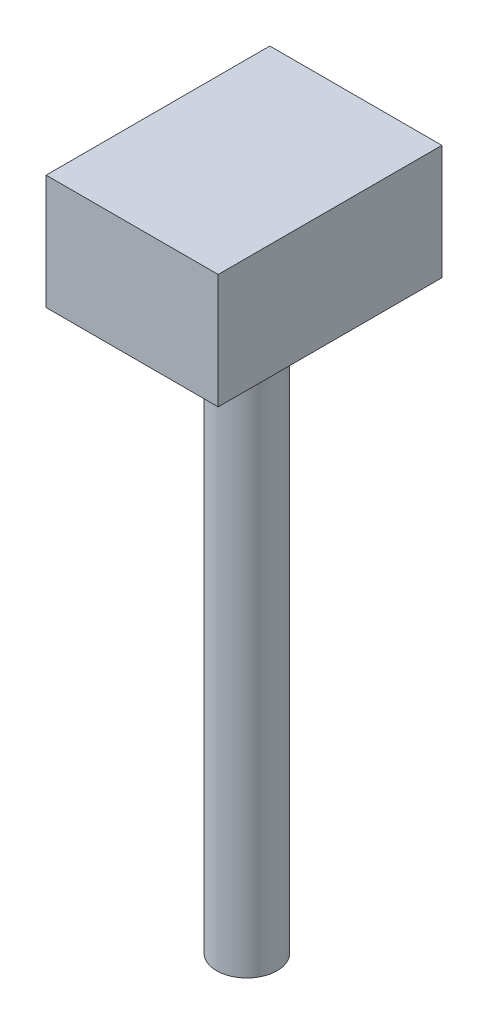
SolidWorks part; units mm, degrees
ref_plane "Front Plane" through (0, 0, 0) normal (0, 0, 1) x (1, 0, 0)
ref_plane "Top Plane" through (0, 0, 0) normal (0, 1, 0) x (1, 0, 0)
ref_plane "Right Plane" through (0, 0, 0) normal (1, 0, 0) x (0, 0, -1)
sketch "Sketch6" plane through (0, 0, 0) normal (0, 0, 1) x (1, 0, 0)
  line L1 (-24.9396, 27.929) -> (275.0604, 27.929)
  line L2 (-24.9396, 27.929) -> (-24.9396, -172.071)
  line L3 (-24.9396, -172.071) -> (275.0604, -172.071)
  line L4 (275.0604, 27.929) -> (275.0604, -172.071)
  dimension "D1" = 200
  dimension "D2" = 300
extrude "Boss-Extrude2" add sketch "Sketch6" along normal blind 400
sketch "Sketch7" plane through (0, 0, 0) normal (0, 0, -1) x (-1, 0, 0)
  line L0 (24.9396, 27.929) -> (24.9396, -172.071) construction
  line L1 (-265.0604, 22.929) -> (14.9396, 22.929)
  line L2 (-265.0604, 22.929) -> (-265.0604, -167.071)
  line L3 (-265.0604, -167.071) -> (14.9396, -167.071)
  line L4 (14.9396, 22.929) -> (14.9396, -167.071)
  line L5 (24.9396, -172.071) -> (-275.0604, -172.071) construction
  dimension "D1" = 280
  dimension "D2" = 190
  dimension "D3" = 10
  dimension "D4" = 5
extrude "Cut-Extrude1" cut sketch "Sketch7" against normal blind 390
sketch "Sketch8" plane through (0, -172.071, 0) normal (0, -1, 0) x (1, 0, 0)
  line L0 (275.0604, 400) -> (275.0604, 0) construction
  line L1 (-24.9396, 0) -> (275.0604, 0) construction
  circle A0 centre (125.0604, 200) radius 52.8065
  dimension "D1" = 150
  dimension "D2" = 200
extrude "Boss-Extrude3" add sketch "Sketch8" along normal blind 1000
sketch "Sketch9" plane through (0, -172.071, 0) normal (0, -1, 0) x (1, 0, 0)
  line L0 (-24.9396, 400) -> (275.0604, 400) construction
  line L2 (125.0604, 400) -> (125.0604, 349.9292) construction
  line L3 (275.0604, 200) -> (184.0714, 200) construction
  line L4 (275.0604, 400) -> (275.0604, 0) construction
  circle A2 centre (45.0604, 15) radius 3.5
  circle A3 centre (205.0604, 15) radius 3.5
extrude "Cut-Extrude3" cut sketch "Sketch9" against normal up to surface (5 mm away) up to face at (125.0604, -167.071, 195)
sketch "Sketch10" plane through (0, -172.071, 0) normal (0, -1, 0) x (1, 0, 0)
  line L0 (-24.9396, 0) -> (-24.9396, 10)
  line L1 (-24.9396, 400) -> (-24.9396, 0) construction
  line L2 (-24.9396, 10) -> (275.0604, 10)
  line L3 (275.0604, 400) -> (275.0604, 0) construction
  line L4 (275.0604, 10) -> (275.0604, 0)
  line L5 (275.0604, 0) -> (-24.9396, 0)
  dimension "D1" = 10
extrude "Cut-Extrude4" cut sketch "Sketch10" against normal up to surface (200 mm away) up to face at (125.0604, 27.929, 200)
